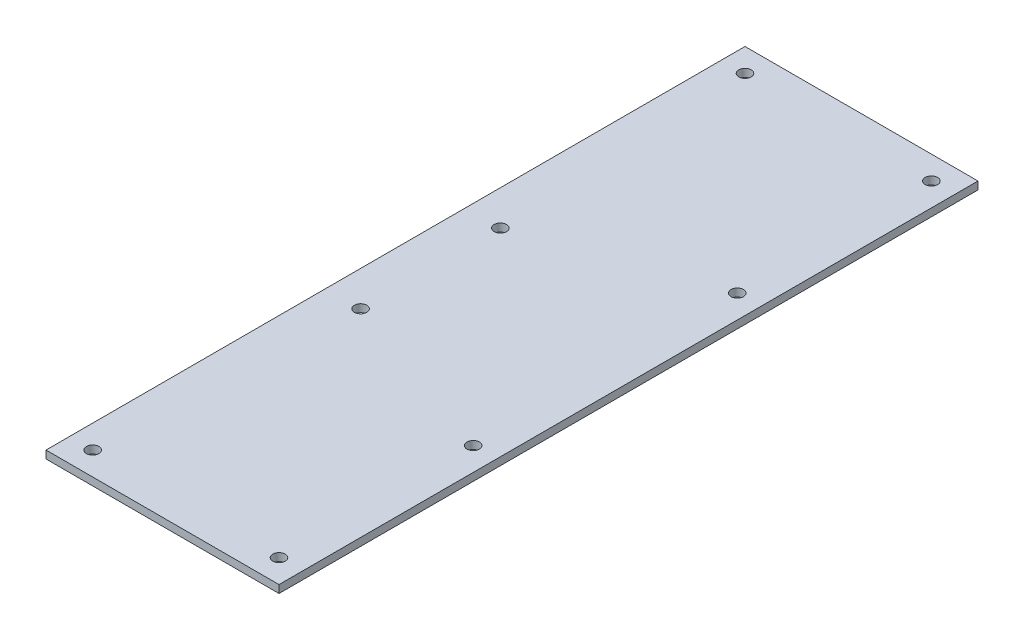
SolidWorks part; units mm, degrees
ref_plane "前视基准面" through (0, 0, 0) normal (0, 0, 1) x (1, 0, 0)
ref_plane "上视基准面" through (0, 0, 0) normal (0, 1, 0) x (1, 0, 0)
ref_plane "右视基准面" through (0, 0, 0) normal (1, 0, 0) x (0, 0, -1)
sketch "草图1" plane through (0, 0, 0) normal (0, 1, 0) x (1, 0, 0)
  line L0 (60, 90) -> (0, 90) construction
  line L1 (0, 0) -> (60, 0)
  line L2 (0, 0) -> (0, 180)
  line L3 (0, 180) -> (60, 180)
  line L4 (60, 0) -> (60, 180)
  line L5 (30, 180) -> (30, -9.4439) construction
  circle A1 centre (54, 56) radius 1.6
  circle A2 centre (54, 124) radius 1.6
  circle A3 centre (9, 108) radius 1.6
  circle A4 centre (9, 72) radius 1.6
  circle A5 centre (6, 174) radius 1.6
  circle A6 centre (54, 174) radius 1.6
  circle A7 centre (54, 6) radius 1.6
  circle A8 centre (6, 6) radius 1.6
  dimension "D3" = 6
  dimension "D4" = 3.2
  dimension "D5" = 45
  dimension "D6" = 16
  dimension "D7" = 68
  dimension "D8" = 3.2
  dimension "D9" = 6
  dimension "D10" = 6
  dimension "D1" = 60
  dimension "D2" = 180
extrude "凸台-拉伸1" add sketch "草图1" along normal blind 2
